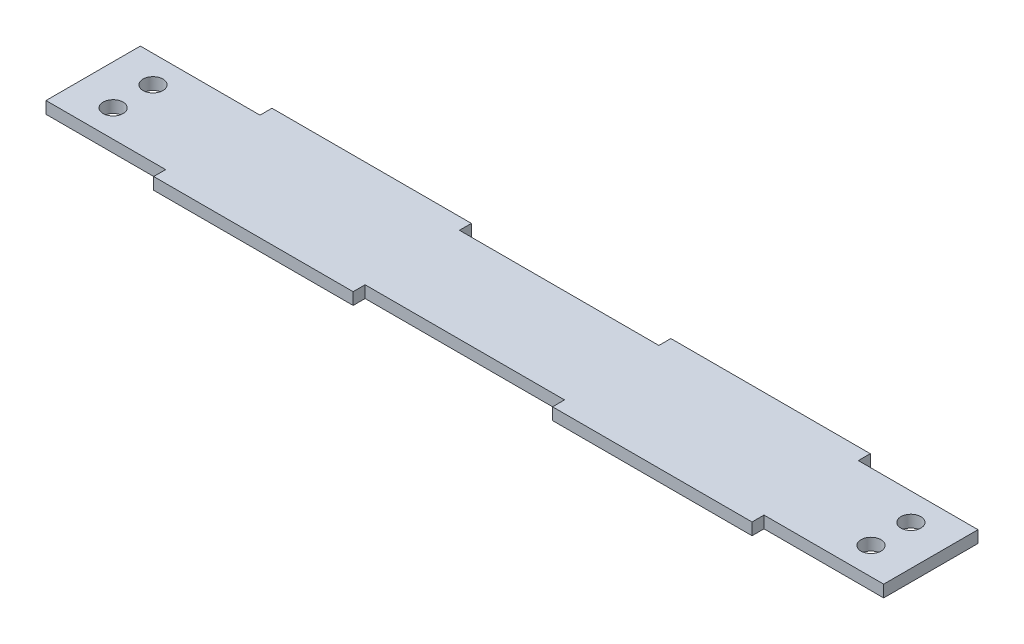
SolidWorks part; units mm, degrees
ref_plane "Front Plane" through (0, 0, 0) normal (0, 0, 1) x (1, 0, 0)
ref_plane "Top Plane" through (0, 0, 0) normal (0, 1, 0) x (1, 0, 0)
ref_plane "Right Plane" through (0, 0, 0) normal (1, 0, 0) x (0, 0, -1)
sketch "Sketch1" plane through (0, 0, 0) normal (0, 1, 0) x (1, 0, 0)
  line L40 (-105, -11.825) -> (-75, -11.825)
  line L41 (-75, -11.825) -> (-75, -14.825)
  line L42 (-75, -14.825) -> (-25, -14.825)
  line L43 (-25, -14.825) -> (-25, -11.825)
  line L44 (-25, -11.825) -> (25, -11.825)
  line L45 (25, -11.825) -> (25, -14.825)
  line L46 (25, -14.825) -> (75, -14.825)
  line L47 (75, -14.825) -> (75, -11.825)
  line L48 (75, -11.825) -> (105, -11.825)
  line L49 (105, -11.825) -> (105, 11.825)
  line L50 (105, 11.825) -> (75, 11.825)
  line L51 (75, 11.825) -> (75, 14.825)
  line L52 (75, 14.825) -> (25, 14.825)
  line L53 (25, 14.825) -> (25, 11.825)
  line L54 (25, 11.825) -> (-25, 11.825)
  line L55 (-25, 11.825) -> (-25, 14.825)
  line L56 (-25, 14.825) -> (-75, 14.825)
  line L57 (-75, 14.825) -> (-75, 11.825)
  line L58 (-75, 11.825) -> (-105, 11.825)
  line L59 (-105, 11.825) -> (-105, -11.825)
  circle A0 centre (-95, 5) radius 2.5
  circle A1 centre (-95, -5) radius 2.5
  circle A2 centre (95, 5) radius 2.5
  circle A3 centre (95, -5) radius 2.5
extrude "Boss-Extrude1" add sketch "Sketch1" along normal blind 3
